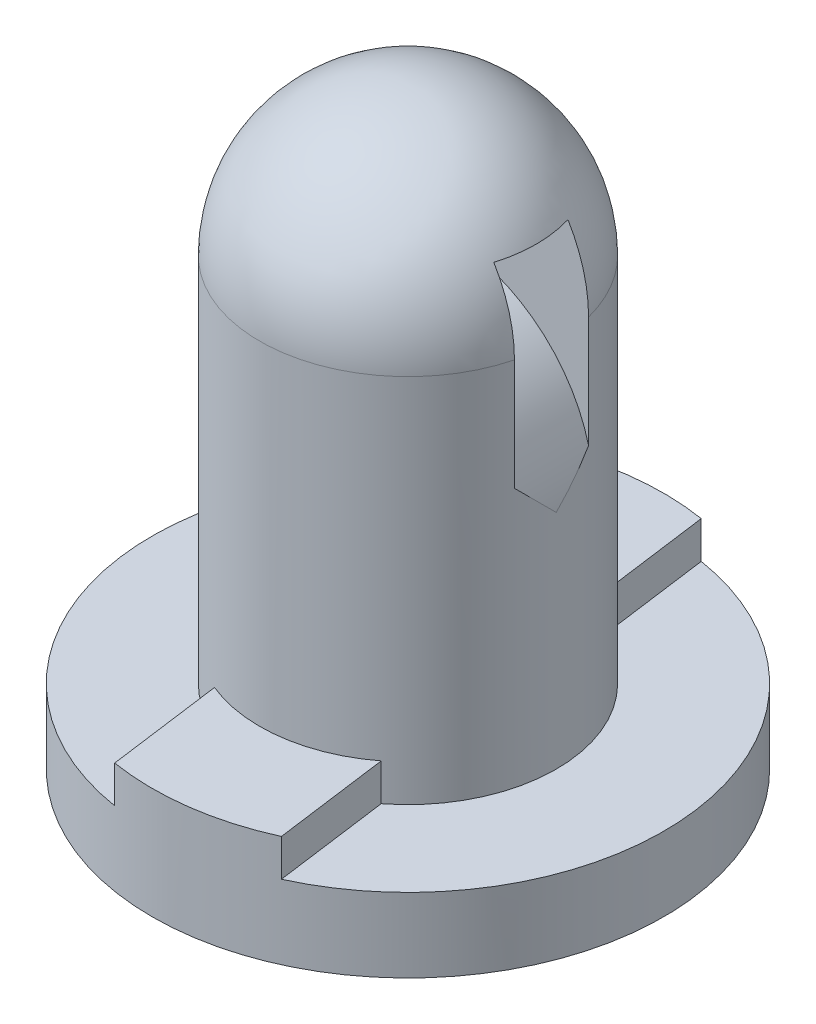
SolidWorks part; units mm, degrees
ref_plane "Front Plane" through (0, 0, 0) normal (0, 0, 1) x (1, 0, 0)
ref_plane "Top Plane" through (0, 0, 0) normal (0, 1, 0) x (1, 0, 0)
ref_plane "Right Plane" through (0, 0, 0) normal (1, 0, 0) x (0, 0, -1)
sketch "Sketch2" plane through (0, 0, 0) normal (0, 1, 0) x (1, 0, 0)
  circle A0 centre (0, 0) radius 3.45
  dimension "D1" = 6.9
extrude "Boss-Extrude1" add sketch "Sketch2" along normal blind 1
sketch "Sketch4" plane through (0, 1, 0) normal (0, 1, 0) x (1, 0, 0)
  circle A0 centre (0, 0) radius 2
  dimension "D1" = 4
extrude "Boss-Extrude2" add sketch "Sketch4" along normal blind 5
sketch "Sketch5" plane through (0, 0, 0) normal (1, 0, 0) x (0, 0, -1)
  line L0 (0, 0) -> (-1, 0)
  line L1 (-1, 0) -> (-2, 6)
  line L2 (0, 0) -> (0, 8)
  arc A0 (-2, 6) -> (0, 8) centre (0, 6) cw
  dimension "D2" = 2
  dimension "D1" = 1
  dimension "D3" = 8
revolve "Revolve1" add sketch "Sketch5" angle 360 about L2
sketch "Sketch8" plane through (0, 0, 0) normal (0, 0, 1) x (1, 0, 0)
  line L0 (-2, 4) -> (-2, 7)
  line L1 (-2, 7) -> (2, 7)
  line L2 (2, 7) -> (2, 4)
  line L5 (-3.45, 0) -> (3.45, 0) construction
  line L6 (-2, 6) -> (-2, 1) construction
  arc A0 (-2, 4) -> (2, 4) centre (0, 4) cw
  point P20 (0, 6)
  dimension "D1" = 2
  dimension "D3" = 1
  dimension "D2" = 4
extrude "Cut-Extrude1" cut sketch "Sketch8" against normal mid plane 1
sketch "Sketch10" plane through (0, 1, 0) normal (0, 1, 0) x (1, 0, 0)
  line L0 (-1.4319, 3.1388) -> (-0.5502, -3.4058)
  line L1 (0.5502, 3.4058) -> (1.4319, -3.1388)
  circle A0 centre (0, 0) radius 3.45 construction
  arc A1 (-1.4319, 3.1388) -> (0.5502, 3.4058) centre (0, 0) cw
  arc A2 (-0.5502, -3.4058) -> (1.4319, -3.1388) centre (0, 0) ccw
  dimension "D1" = 2
extrude "Boss-Extrude3" add sketch "Sketch10" along normal blind 0.5
